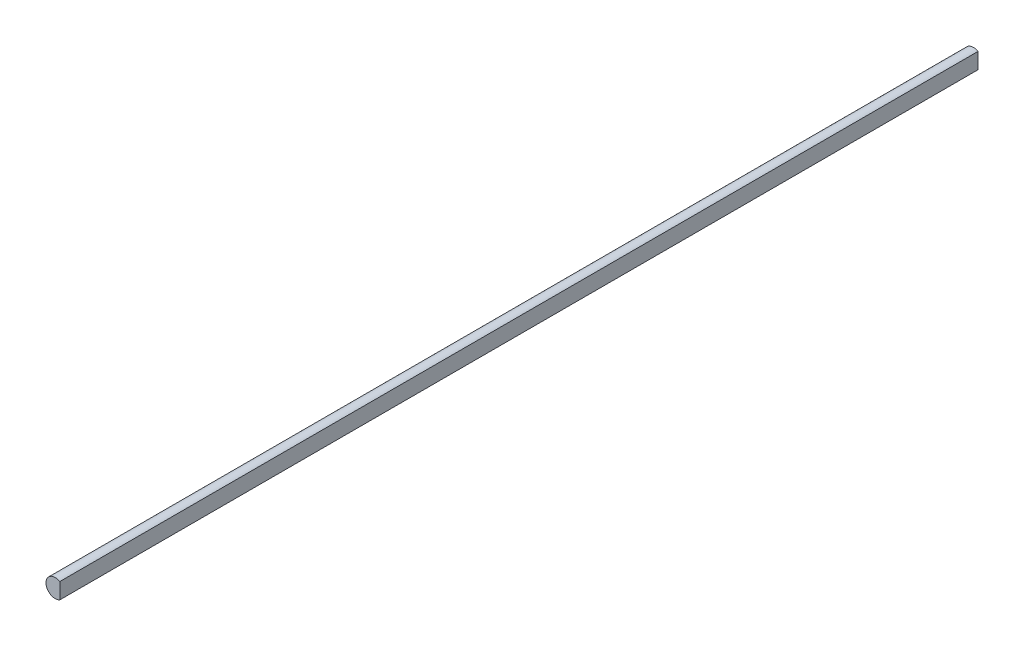
SolidWorks part; units mm, degrees
ref_plane "Front Plane" through (0, 0, 0) normal (0, 0, 1) x (1, 0, 0)
ref_plane "Top Plane" through (0, 0, 0) normal (0, 1, 0) x (1, 0, 0)
ref_plane "Right Plane" through (0, 0, 0) normal (1, 0, 0) x (0, 0, -1)
sketch "Sketch1" plane through (0, 0, 0) normal (0, 0, 1) x (1, 0, 0)
  line L0 (0.75, 1.299) -> (0.75, -1.299)
  arc A0 (0.75, 1.299) -> (0.75, -1.299) centre (0, 0) ccw
  dimension "D1" = 1.5
  dimension "D2" = 0.75
extrude "Boss-Extrude1" add sketch "Sketch1" along normal blind 150
